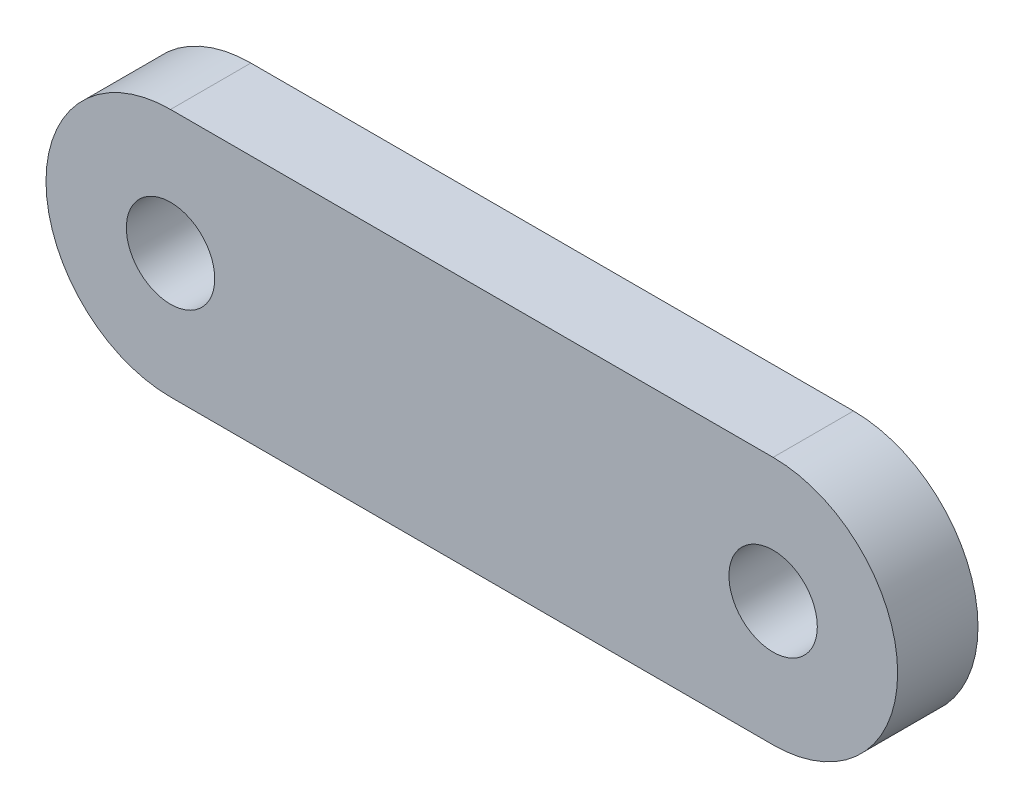
SolidWorks part; units mm, degrees
ref_plane "Спереди" through (0, 0, 0) normal (0, 0, 1) x (1, 0, 0)
ref_plane "Сверху" through (0, 0, 0) normal (0, 1, 0) x (1, 0, 0)
ref_plane "Справа" through (0, 0, 0) normal (1, 0, 0) x (0, 0, -1)
sketch "Эскиз1" plane through (0, 0, 0) normal (0, 0, 1) x (1, 0, 0)
  line L0 (0, -11.0883) -> (0, 11.0883) construction
  line L1 (-11.25, -4.65) -> (11.25, -4.65)
  line L2 (-11.25, -4.65) -> (-11.25, 4.65)
  line L3 (-11.25, 4.65) -> (11.25, 4.65)
  line L4 (11.25, -4.65) -> (11.25, 4.65)
  line L5 (-11.25, -4.65) -> (11.25, 4.65) construction
  line L6 (-11.25, 4.65) -> (11.25, -4.65) construction
  circle A0 centre (-11.25, 0) radius 4.65
  circle A1 centre (11.25, 0) radius 4.65
  circle A2 centre (-11.25, 0) radius 1.65
  circle A3 centre (11.25, 0) radius 1.65
  point P0 (0, 0)
  dimension "D2" = 3.3
  dimension "D3" = 3
  dimension "D1" = 22.5
extrude "Бобышка-Вытянуть1" add sketch "Эскиз1" along normal blind 3 contours L1 A1 L3 A0 | A3 L4 A1 | A3 L4 A1 | A2 L2 A0 | A2 L2 A0
